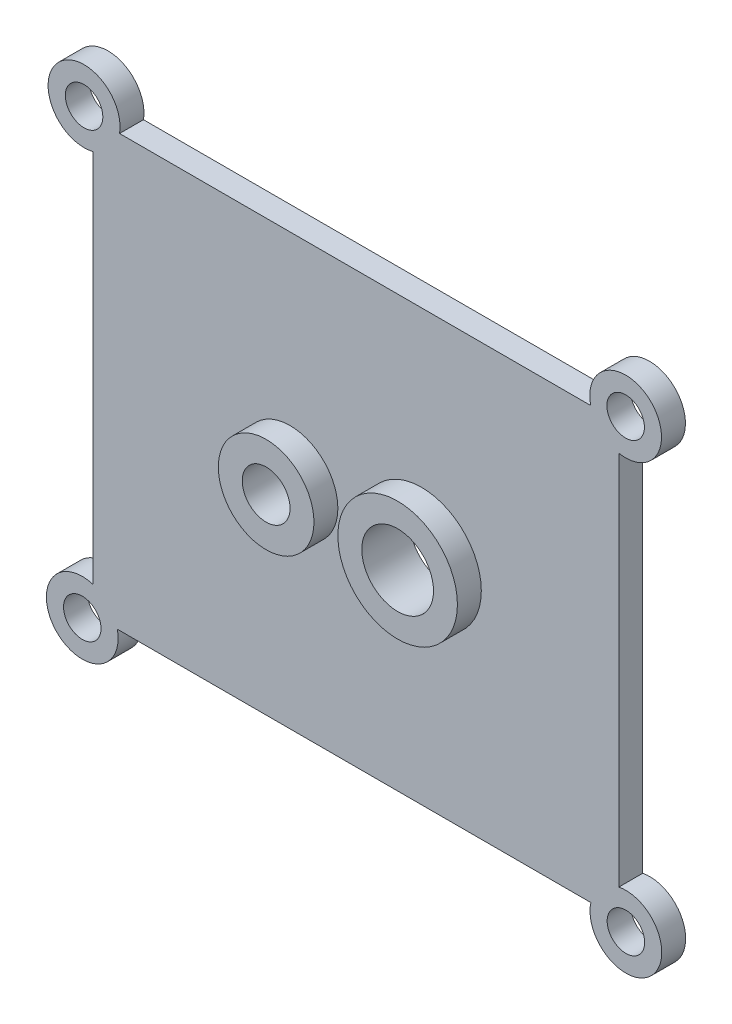
SolidWorks part; units mm, degrees
ref_plane "Front Plane" through (0, 0, 0) normal (0, 0, 1) x (1, 0, 0)
ref_plane "Top Plane" through (0, 0, 0) normal (0, 1, 0) x (1, 0, 0)
ref_plane "Right Plane" through (0, 0, 0) normal (1, 0, 0) x (0, 0, -1)
sketch "Sketch1" plane through (0, 0, 0) normal (0, 0, 1) x (1, 0, 0)
  line L1 (-34.925, -28.575) -> (34.925, -28.575)
  line L2 (-34.925, -28.575) -> (-34.925, 28.575)
  line L3 (-34.925, 28.575) -> (34.925, 28.575)
  line L4 (34.925, -28.575) -> (34.925, 28.575)
  line L5 (-34.925, -28.575) -> (34.925, 28.575) construction
  line L6 (-34.925, 28.575) -> (34.925, -28.575) construction
  point P0 (0, 0)
  dimension "D1" = 69.85
  dimension "D2" = 57.15
extrude "Boss-Extrude1" add sketch "Sketch1" along normal blind 3.175
sketch "Sketch2" plane through (0, 0, 3.175) normal (0, 0, 1) x (1, 0, 0)
  circle A0 centre (-36.0809, 29.3595) radius 4.7767
  circle A1 centre (35.8327, 29.637) radius 4.7625
  circle A2 centre (35.8648, -29.6086) radius 4.7625
  circle A3 centre (-36.322, -29.5906) radius 4.7625
extrude "Boss-Extrude2" add sketch "Sketch2" against normal blind 3.175
sketch "Sketch3" plane through (0, 0, 3.175) normal (0, 0, 1) x (1, 0, 0)
  circle A0 centre (-36.0809, 29.3595) radius 2.4892
  circle A1 centre (35.8327, 29.637) radius 2.4892
  circle A2 centre (35.8648, -29.6086) radius 2.4892
  circle A3 centre (-36.322, -29.5906) radius 2.4892
  dimension "D1" = 4.9784
extrude "Cut-Extrude1" cut sketch "Sketch3" against normal through all
sketch "Sketch4" plane through (0, 0, 3.175) normal (0, 0, 1) x (1, 0, 0)
  line L0 (0, 0) -> (-34.925, -0.1564) construction
  line L2 (-34.925, 24.7247) -> (-34.925, -25.0376) construction
  line L3 (0, 0) -> (-0.2266, -28.575) construction
  line L4 (-31.669, -28.575) -> (31.2158, -28.575) construction
  line L5 (0, 0) -> (34.925, 0.011) construction
  line L6 (34.925, -24.9398) -> (34.925, 24.9618) construction
  line L7 (0, 0) -> (-0.0895, 28.575) construction
  line L8 (31.1901, 28.575) -> (-31.3691, 28.575) construction
  circle A0 centre (-8.7312, -0.0391) radius 3.175
  circle A1 centre (8.7312, 0.0027) radius 4.7625
  point P4 (-8.7312, -0.0391)
  point P12 (8.7312, 0.0027)
  dimension "D3" = 6.35
  dimension "D4" = 9.525
  dimension "D1" = 8.7312
  dimension "D2" = 8.7312
extrude "Cut-Extrude2" cut sketch "Sketch4" against normal through all
sketch "Sketch5" plane through (0, 0, 3.175) normal (0, 0, 1) x (1, 0, 0)
  circle A0 centre (-8.7312, -0.0391) radius 6.35
  circle A1 centre (8.7312, 0.0027) radius 7.9375
  dimension "D1" = 12.7
  dimension "D2" = 15.875
extrude "Boss-Extrude3" add sketch "Sketch5" along normal blind 3.175
sketch "Sketch6" plane through (0, 0, 6.35) normal (0, 0, 1) x (1, 0, 0)
  circle A0 centre (8.7312, 0.0027) radius 4.7625
  circle A1 centre (-8.7312, -0.0391) radius 3.175
  dimension "D1" = 6.35
  dimension "D2" = 9.525
extrude "Cut-Extrude3" cut sketch "Sketch6" against normal through all
